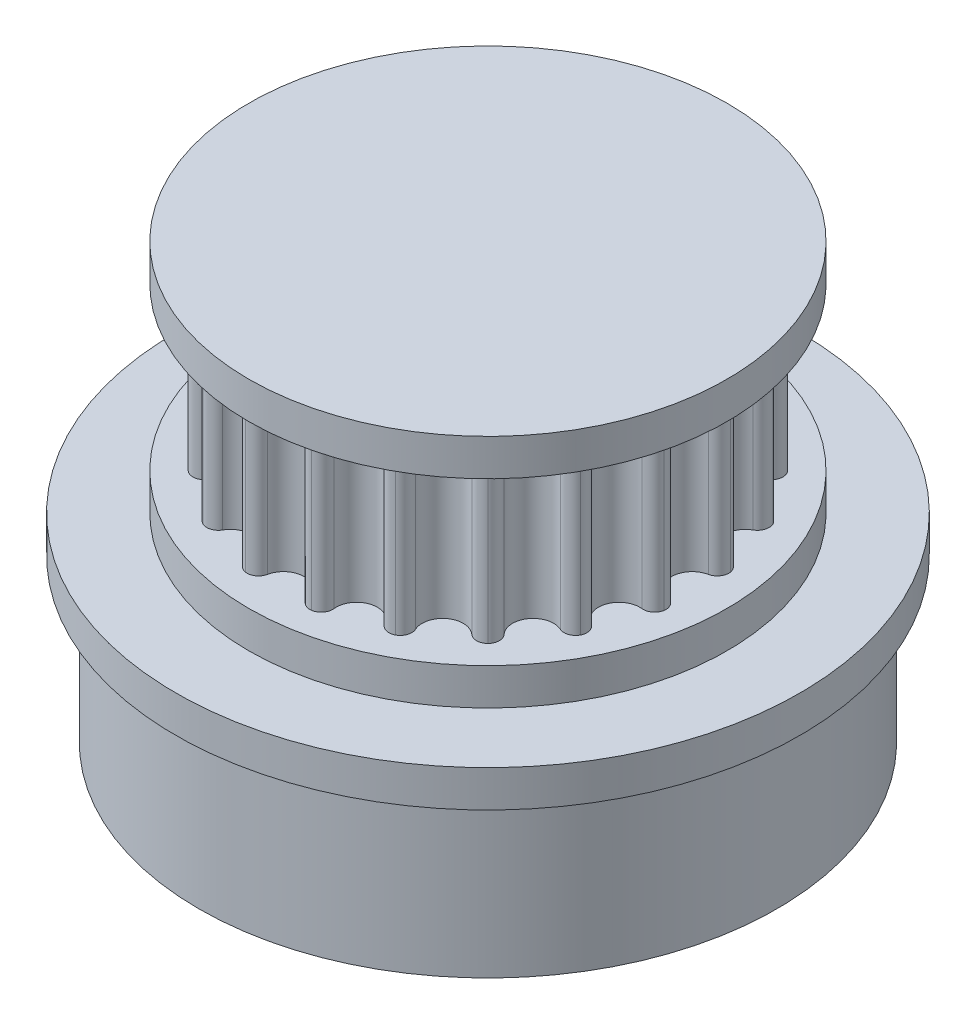
SolidWorks part; units mm, degrees
ref_plane "Front Plane" through (0, 0, 0) normal (0, 0, 1) x (1, 0, 0)
ref_plane "Top Plane" through (0, 0, 0) normal (0, 1, 0) x (1, 0, 0)
ref_plane "Right Plane" through (0, 0, 0) normal (1, 0, 0) x (0, 0, -1)
sketch "Sketch1" plane through (0, 0, 0) normal (0, 1, 0) x (1, 0, 0)
  line L0 (0, 0) -> (0, 9.1676) construction
  line L1 (0, 0) -> (2.731, 8.405) construction
  circle A0 centre (0, 0) radius 9.1676 construction
  circle A1 centre (0, 0) radius 7.9476 construction
  circle A2 centre (0, 8.8376) radius 0.89 construction
  circle A5 centre (2.731, 8.405) radius 0.89 construction
  arc A6 (0, 7.9476) -> (0.8721, 8.6598) centre (0, 8.8376) ccw
  arc A7 (0.8721, 8.6598) -> (1.4405, 9.0537) centre (1.362, 8.5599) cw
  arc A8 (1.4277, 9.0557) -> (1.8466, 8.5054) centre (1.3498, 8.5618) cw
  arc A9 (2.4559, 7.5586) -> (1.8466, 8.5054) centre (2.731, 8.405) cw
  arc A10 (1.4405, 9.0537) -> (1.4277, 9.0557) centre (0, 0) cw
  arc A11 (0, 7.9476) -> (2.4559, 7.5586) centre (0, 0) ccw
  dimension "D1" = 18.3352
  dimension "D3" = 1.78
  dimension "D4" = 0.5
  dimension "D2" = 1.22
  dimension "D5" = 18
extrude "Boss-Extrude1" add sketch "Sketch1" along normal mid plane 7 contours A6 A11 A9 A8 A7
ref_axis "Axis1" through (0, 3.3, 0) along (0, -1, 0)
pattern_circular "CirPattern1" count 20 over 360 about axis through (0, 0, 0) along (0, 1, 0) of "Boss-Extrude1"
sketch "Sketch2" plane through (0, 0, 0) normal (1, 0, 0) x (0, 0, -1)
  line L10 (0, 3.5) -> (10.3423, 3.5) construction
  line L11 (0, 3.5) -> (0, 5.0875) construction
  line L12 (0, 5.0875) -> (10.3423, 5.0875) construction
  line L15 (10.3423, 3.5) -> (10.3423, 5.0875) construction
  line L20 (0, 3.3) -> (0, -3.3) construction
  line L22 (10.3423, 5.0875) -> (0, 5.0875)
  line L23 (10.3423, 5.0875) -> (10.3423, 3.5)
  line L24 (10.3423, 3.5) -> (0, 3.5)
  line L25 (0, 5.0875) -> (0, 3.5)
  dimension "D1" = 1.5875
  dimension "D2" = 10.3423
  dimension "D3" = 3.5
revolve "Revolve3" add sketch "Sketch2" angle 360 about axis through (0, 3.3, 0) along (0, -1, 0)
mirror "Mirror1" about plane through (0, 0, 0) normal (0, 1, 0) of "Revolve3"
sketch "Sketch3" plane through (0, 0, 0) normal (0, -1, 0) x (-1, 0, 0)
  circle A0 centre (0, 0) radius 3.1986
  dimension "D1" = 6.3972
extrude "Cut-Extrude1" [suppressed] cut sketch "Sketch3" against normal through all both and the other way through all
sketch "Sketch5" plane through (0, 0, 0) normal (0, 0, 1) x (1, 0, 0)
  line L0 (0, -5.0875) -> (13.5, -5.0875)
  line L1 (-10.3423, -5.0875) -> (10.3423, -5.0875) construction
  line L2 (13.5, -5.0875) -> (13.5, -6.675)
  line L3 (13.5, -6.675) -> (12.5, -6.675)
  line L4 (12.5, -6.675) -> (12.5, -13.675)
  line L5 (12.5, -13.675) -> (0, -13.675)
  line L6 (0, -13.675) -> (0, -5.0875) construction
  line L7 (0, -5.0875) -> (0, -13.675)
  point P6 (13.5, -5.8812)
  dimension "D2" = 25
  dimension "D3" = 1.5875
  dimension "D4" = 7
  dimension "D1" = 1
revolve "Revolve4" add sketch "Sketch5" angle 360 about L6
equation "\"TEETH_NUM\"= 20"
equation "\"TOOTH_PITCH\"= 3mm"
equation "\"PITCH_LINE_OFFSET\"= .015in"
equation "\"DIAMETER_PER_GROOVE\"= \"OUTSIDE_DIAMETER\" / \"TEETH_NUM\" * 1in"
equation "\"PITCH_DIAMETER\"= ( ( \"TEETH_NUM\" * 3 - 1.31 ) / 3.1415 + .415 ) * 1mm"
equation "\"OUTSIDE_DIAMETER\"= \"PITCH_DIAMETER\" - \"PITCH_LINE_OFFSET\" * 2"
equation "\"D1@Sketch1\"=\"OUTSIDE_DIAMETER\""
equation "\"TOOTH_HEIGHT\"= 1.22mm"
equation "\"D2@Sketch1\"=\"TOOTH_HEIGHT\""
equation "\"TOOTH_DIAMETER\"= 1.78mm"
equation "\"INTERNAL_RADIUS\"= .5mm"
equation "\"D3@Sketch1\"=\"TOOTH_DIAMETER\""
equation "\"D5@Sketch1\"=360 / \"TEETH_NUM\""
equation "\"D4@Sketch1\"=\"INTERNAL_RADIUS\""
equation "\"D1@CirPattern1\"=\"TEETH_NUM\""
equation "\"BELT_GAP\"= 7mm"
equation "\"D2@Sketch2\"=\"PITCH_DIAMETER\"/2+1/32"
equation "\"D3@Sketch2\"=\"BELT_GAP\"/2"
equation "\"D1@Sketch3\"=\"PITCH_DIAMETER\"-.5"
equation "\"D1@Boss-Extrude1\"=\"BELT_GAP\""
equation "\"bearing_heigh\" = 7mm"
equation "\"D4@Sketch5\"=\"bearing_heigh\""
equation "\"bearing_ID\" = 25mm"
equation "\"flange\"= 1mm"
equation "\"D1@Sketch5\"=\"flange\""
